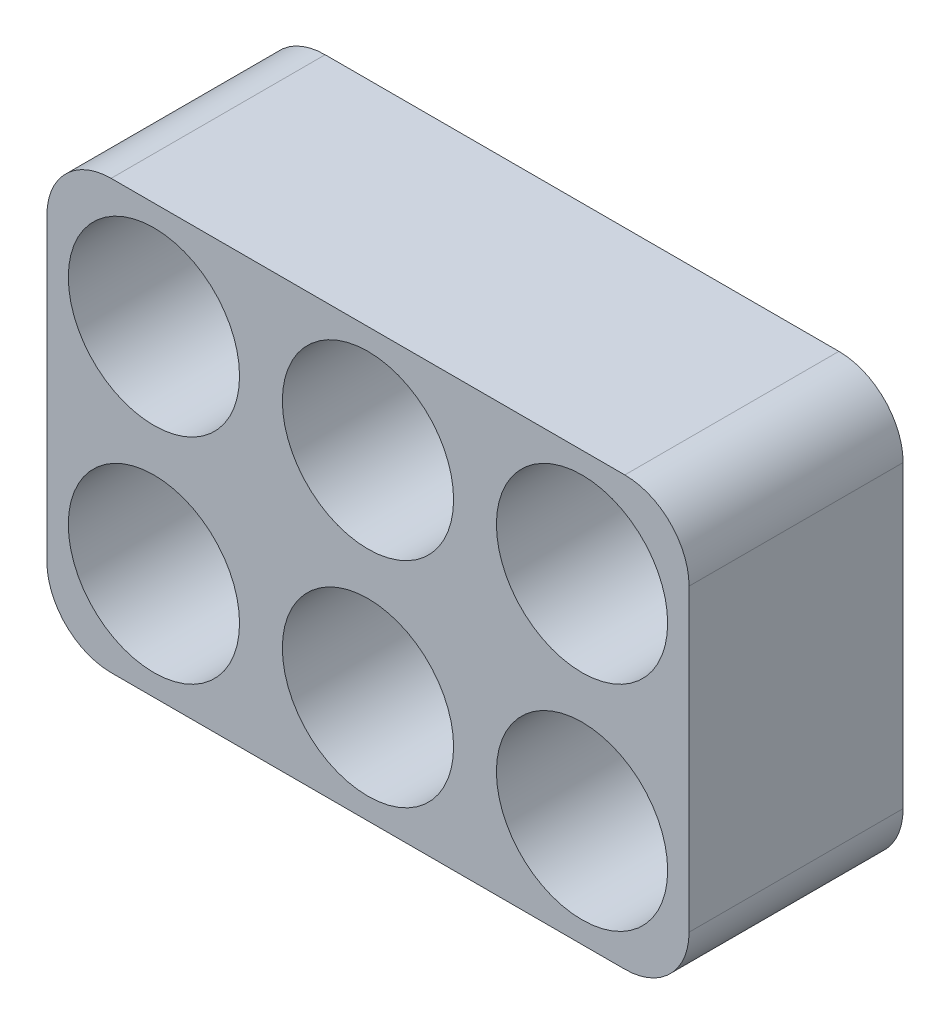
SolidWorks part; units mm, degrees
ref_plane "前视基准面" through (0, 0, 0) normal (0, 0, 1) x (1, 0, 0)
ref_plane "上视基准面" through (0, 0, 0) normal (0, 1, 0) x (1, 0, 0)
ref_plane "右视基准面" through (0, 0, 0) normal (1, 0, 0) x (0, 0, -1)
other "Configuration Table"
sketch "草图1" plane through (0, 0, 0) normal (0, 0, 1) x (1, 0, 0)
  line L1 (-12, -10) -> (12, -10)
  line L2 (-15, -7) -> (-15, 7)
  line L3 (-12, 10) -> (12, 10)
  line L4 (15, -7) -> (15, 7)
  line L5 (-15, -10) -> (15, 10) construction
  line L6 (-15, 10) -> (15, -10) construction
  line L7 (-10, -5) -> (10, -5) construction
  line L8 (-10, -5) -> (-10, 5) construction
  line L9 (-10, 5) -> (10, 5) construction
  line L10 (10, -5) -> (10, 5) construction
  line L11 (-10, -5) -> (10, 5) construction
  line L12 (-10, 5) -> (10, -5) construction
  circle A0 centre (-10, 5) radius 4
  circle A1 centre (0, 5) radius 4
  circle A2 centre (10, 5) radius 4
  circle A3 centre (0, -5) radius 4
  circle A4 centre (10, -5) radius 4
  circle A5 centre (-10, -5) radius 4
  arc A6 (-12, -10) -> (-15, -7) centre (-12, -7) cw
  arc A7 (12, -10) -> (15, -7) centre (12, -7) ccw
  arc A8 (12, 10) -> (15, 7) centre (12, 7) cw
  arc A9 (-15, 7) -> (-12, 10) centre (-12, 7) cw
  point P0 (0, 0)
  point P6 (0, 0)
  dimension "D5" = 8
  dimension "D8" = 3
  dimension "D1" = 30
  dimension "D2" = 20
  dimension "D3" = 20
  dimension "D4" = 10
  dimension "D6" = 3
  dimension "D7" = 2
extrude "凸台-拉伸1" add sketch "草图1" along normal blind 10
